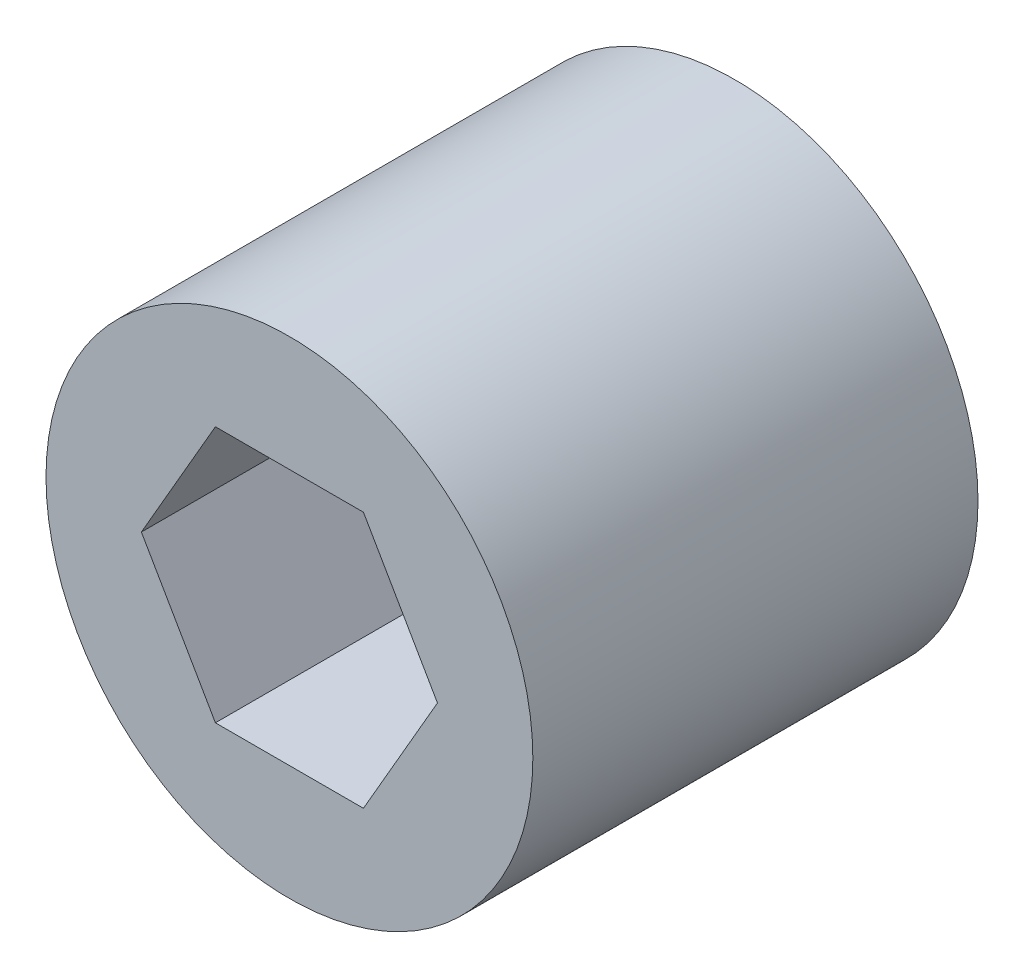
SolidWorks part; units mm, degrees
material "Nylon 101"
ref_plane "Front Plane" through (0, 0, 0) normal (0, 0, 1) x (1, 0, 0)
ref_plane "Top Plane" through (0, 0, 0) normal (0, 1, 0) x (1, 0, 0)
ref_plane "Right Plane" through (0, 0, 0) normal (1, 0, 0) x (0, 0, -1)
sketch "Sketch1" plane through (0, 0, 0) normal (0, 0, 1) x (1, 0, 0)
  line L1 (-5.7926, 0) -> (-2.8963, -5.0165)
  line L2 (-2.8963, -5.0165) -> (2.8963, -5.0165)
  line L3 (2.8963, -5.0165) -> (5.7926, 0)
  line L4 (5.7926, 0) -> (2.8963, 5.0165)
  line L5 (2.8963, 5.0165) -> (-2.8963, 5.0165)
  line L6 (-2.8963, 5.0165) -> (-5.7926, 0)
  circle A0 centre (0, 0) radius 9.525
  circle A2 centre (0, 0) radius 5.0165 construction
  point P3 (0, 0)
  dimension "D1" = 19.05
  dimension "D2" = 10.033
extrude "Boss-Extrude1" add sketch "Sketch1" along normal mid plane 17.4185
equation "\"D1@Boss-Extrude1\"=0.0625in+0.45mm/2"
